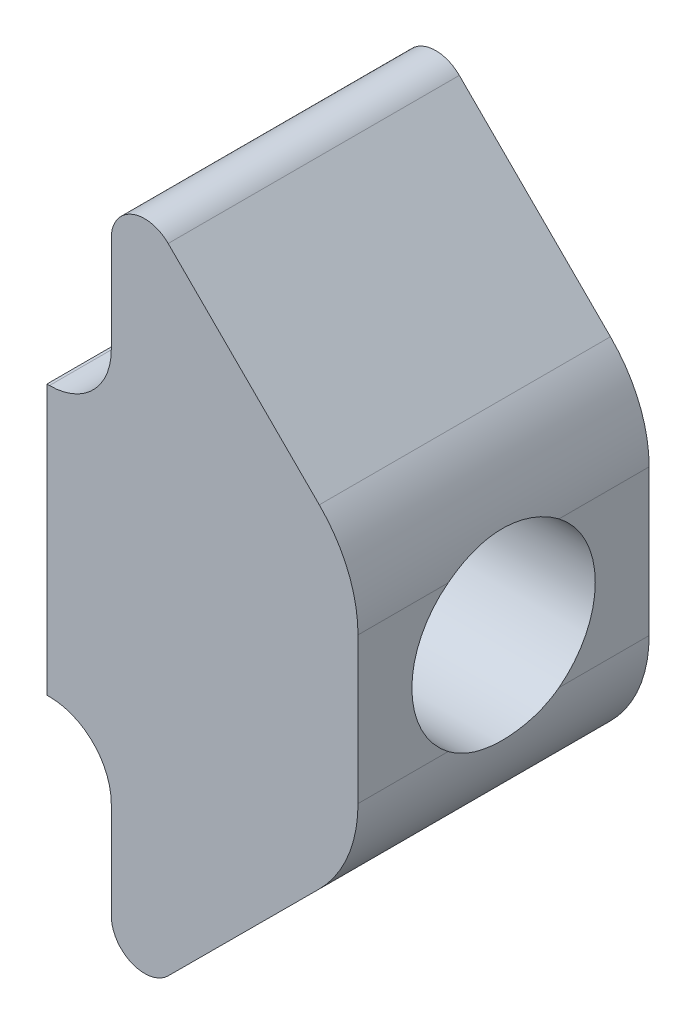
SolidWorks part; units mm, degrees
ref_plane "Front Plane" through (0, 0, 0) normal (0, 0, 1) x (1, 0, 0)
ref_plane "Top Plane" through (0, 0, 0) normal (0, 1, 0) x (1, 0, 0)
ref_plane "Right Plane" through (0, 0, 0) normal (1, 0, 0) x (0, 0, -1)
sketch "Sketch1" plane through (0, 0, 0) normal (0, 0, 1) x (1, 0, 0)
  line L0 (-11.5951, -2.9385) -> (-11.5951, 2.9385)
  line L1 (-11.5951, 2.9385) -> (-11.5392, 2.9385)
  line L2 (-10.1902, 4.2875) -> (-10.1902, 6.4021)
  line L3 (-8.949, 6.917) -> (-5.6529, 3.6284)
  line L4 (-4.8085, 1.5932) -> (-4.8085, -1.5932)
  line L5 (-5.6529, -3.6284) -> (-8.949, -6.917)
  line L6 (-10.1902, -6.4021) -> (-10.1902, -4.2875)
  line L7 (-11.5392, -2.9385) -> (-11.5951, -2.9385)
  line L8 (-11.651, 2.9385) -> (-11.5392, 2.9385) construction
  line L9 (-11.5392, -2.9385) -> (-11.651, -2.9385) construction
  line L10 (-11.5951, -2.9385) -> (-11.9739, -2.9385)
  line L119 (-11.651, 3.2385) -> (-11.5392, 3.2385) construction
  line L120 (-10.4902, 4.2875) -> (-10.4902, 6.4021) construction
  line L121 (-8.7371, 7.1294) -> (-5.441, 3.8408) construction
  line L122 (-4.5085, 1.5932) -> (-4.5085, -1.5932) construction
  line L123 (-5.441, -3.8408) -> (-8.7371, -7.1294) construction
  line L124 (-10.4902, -6.4021) -> (-10.4902, -4.2875) construction
  line L125 (-11.5392, -3.2385) -> (-11.651, -3.2385) construction
  arc A0 (-11.5392, 2.9385) -> (-10.1902, 4.2875) centre (-11.5392, 4.2875) ccw
  arc A1 (-8.949, 6.917) -> (-10.1902, 6.4021) centre (-9.4628, 6.4021) ccw
  arc A2 (-4.8085, 1.5932) -> (-5.6529, 3.6284) centre (-7.6835, 1.5932) ccw
  arc A3 (-5.6529, -3.6284) -> (-4.8085, -1.5932) centre (-7.6835, -1.5932) ccw
  arc A4 (-10.1902, -6.4021) -> (-8.949, -6.917) centre (-9.4628, -6.4021) ccw
  arc A5 (-10.1902, -4.2875) -> (-11.5392, -2.9385) centre (-11.5392, -4.2875) ccw
  arc A142 (-11.5392, 3.2385) -> (-10.4902, 4.2875) centre (-11.5392, 4.2875) ccw construction
  arc A143 (-8.7371, 7.1294) -> (-10.4902, 6.4021) centre (-9.4628, 6.4021) ccw construction
  arc A144 (-4.5085, 1.5932) -> (-5.441, 3.8408) centre (-7.6835, 1.5932) ccw construction
  arc A145 (-5.441, -3.8408) -> (-4.5085, -1.5932) centre (-7.6835, -1.5932) ccw construction
  arc A146 (-10.4902, -6.4021) -> (-8.7371, -7.1294) centre (-9.4628, -6.4021) ccw construction
  arc A147 (-10.4902, -4.2875) -> (-11.5392, -3.2385) centre (-11.5392, -4.2875) ccw construction
  dimension "D1" = 0.3
  dimension "D2" = 5.8769
  dimension "D3" = 0.3788
extrude "Boss-Extrude1" add sketch "Sketch1" along normal blind 6.35 contours L0 L1 A0 L2 A1 L3 A2 L4 A3 L5 A4 L6 A5 L7
sketch "Sketch2" plane through (-11.5951, 0, 0) normal (-1, 0, 0) x (0, 0, 1)
  line L0 (3.175, 2.9385) -> (3.175, -2.9385) construction
  line L1 (6.35, 2.9385) -> (0, 2.9385) construction
  line L2 (6.35, -2.9385) -> (0, -2.9385) construction
  line L3 (0, 0) -> (6.35, 0) construction
  line L4 (0, -2.9385) -> (0, 2.9385) construction
  line L5 (6.35, -2.9385) -> (6.35, 2.9385) construction
  circle A0 centre (3.175, 0) radius 2
  dimension "D1" = 4
extrude "Cut-Extrude1" cut sketch "Sketch2" against normal up to next contours A0
fillet "Fillet1" radius 0.4 1 edges at (-11.5951, 0, 5.175) profile chamfer
